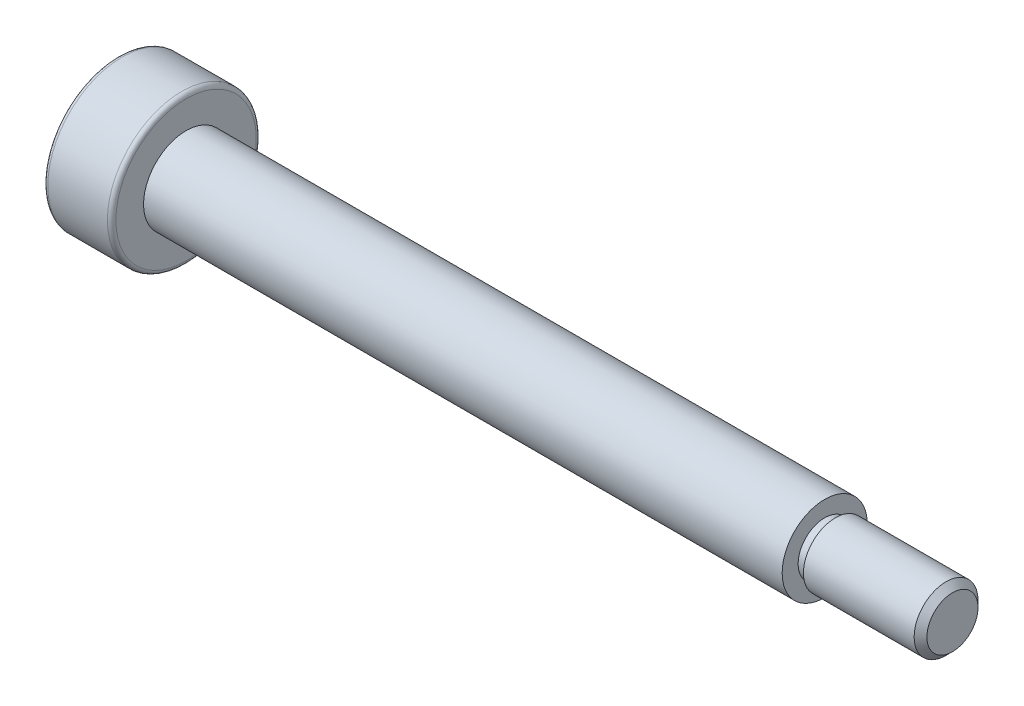
SolidWorks part; units mm, degrees
ref_plane "前视基准面" through (0, 0, 0) normal (0, 0, 1) x (1, 0, 0)
ref_plane "上视基准面" through (0, 0, 0) normal (0, 1, 0) x (1, 0, 0)
ref_plane "右视基准面" through (0, 0, 0) normal (1, 0, 0) x (0, 0, -1)
sketch "草图1" plane through (0, 0, 0) normal (0, 0, 1) x (1, 0, 0)
  line L0 (-19.6, 0) -> (19.6, 0) construction
  line L1 (-19.6, 0) -> (-19.6, 3.5)
  line L2 (-19.6, 3.5) -> (-16.4, 3.5)
  line L3 (-16.4, 3.5) -> (-16.4, 2)
  line L4 (-16.4, 2) -> (13.6, 2)
  line L5 (13.6, 2) -> (13.6, 1.5)
  line L6 (13.6, 1.5) -> (19.6, 1.5)
  line L7 (19.6, 1.5) -> (19.6, 0)
  line L8 (-19.6, 0) -> (19.6, 0)
  dimension "D1" = 4
  dimension "D2" = 7
  dimension "D3" = 3
  dimension "D4" = 6
  dimension "D5" = 30
  dimension "D6" = 3.2
revolve "旋转1" add sketch "草图1" angle 360 about L0
fillet "圆角1" radius 0.2 2 edges at (-16.4, 0, 3.5) (-19.6, 0, 3.5)
chamfer "倒角1" distance 0.3 angle 45 1 edges at (19.6, 0, 1.5)
sketch "草图3" plane through (0, 0, 0) normal (0, 0, 1) x (1, 0, 0)
  line L0 (13.6, 0) -> (19.3, 0) construction
  line L1 (13.6, -1.5) -> (13.6, 1.5) construction
  line L2 (19.3, 1.5) -> (19.3, -1.5) construction
  line L3 (13.6, -2) -> (13.6, 2) construction
  line L4 (13.6, 1.5) -> (14.1, 1.5)
  line L5 (13.6, 1.5) -> (13.6, 1.25)
  line L6 (13.6, 1.25) -> (14.1, 1.25)
  line L7 (14.1, 1.5) -> (14.1, 1.25)
  line L8 (19.3, 1.5) -> (13.6, 1.5) construction
  dimension "D1" = 2.5
  dimension "D2" = 0.5
revolve "切除-旋转1" cut sketch "草图3" angle 360 about L0
sketch "草图4" plane through (-19.6, 0, 0) normal (-1, 0, 0) x (0, 0, 1)
  line L1 (1.7321, 0) -> (0.866, 1.5)
  line L2 (0.866, 1.5) -> (-0.866, 1.5)
  line L3 (-0.866, 1.5) -> (-1.7321, 0)
  line L4 (-1.7321, 0) -> (-0.866, -1.5)
  line L5 (-0.866, -1.5) -> (0.866, -1.5)
  line L6 (0.866, -1.5) -> (1.7321, 0)
  circle A0 centre (0, 0) radius 1.5 construction
  dimension "D1" = 3
extrude "切除-拉伸1" cut sketch "草图4" against normal blind 2
